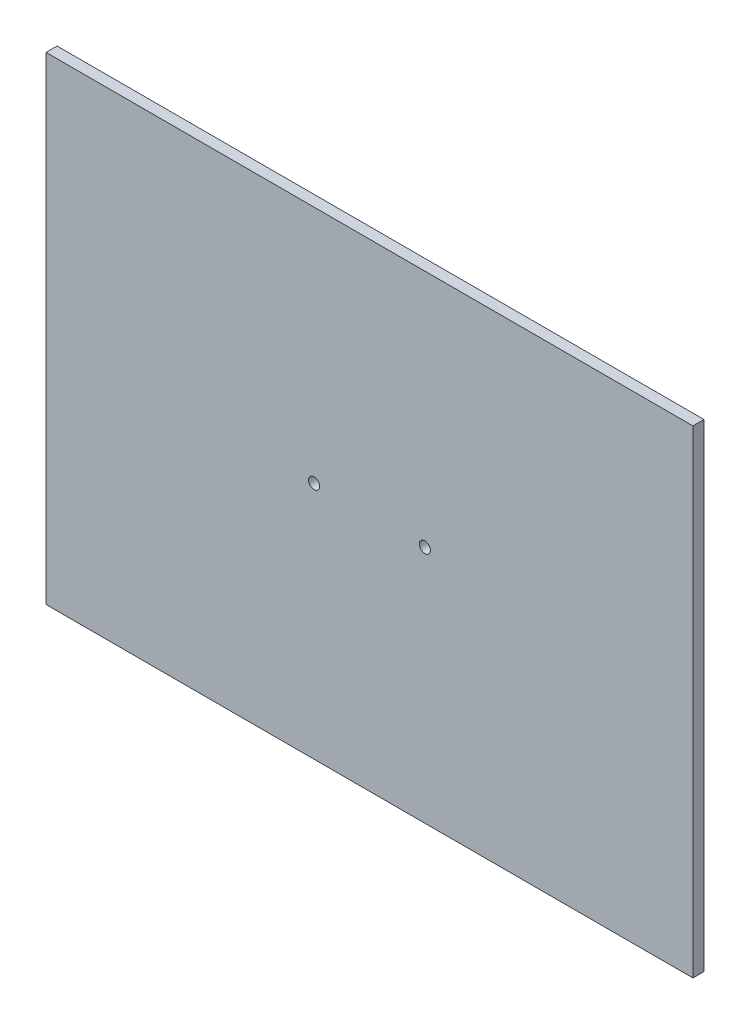
SolidWorks part; units mm, degrees
ref_plane "Front Plane" through (0, 0, 0) normal (0, 0, 1) x (1, 0, 0)
ref_plane "Top Plane" through (0, 0, 0) normal (0, 1, 0) x (1, 0, 0)
ref_plane "Right Plane" through (0, 0, 0) normal (1, 0, 0) x (0, 0, -1)
sketch "Sketch1" plane through (0, 0, 0) normal (0, 0, 1) x (1, 0, 0)
  line L1 (-146.05, -107.95) -> (146.05, -107.95)
  line L2 (-146.05, -107.95) -> (-146.05, 107.95)
  line L3 (-146.05, 107.95) -> (146.05, 107.95)
  line L4 (146.05, -107.95) -> (146.05, 107.95)
  line L5 (-146.05, -107.95) -> (146.05, 107.95) construction
  line L6 (-146.05, 107.95) -> (146.05, -107.95) construction
  point P0 (0, 0)
  dimension "D1" = 215.9
  dimension "D2" = 292.1
extrude "Boss-Extrude1" add sketch "Sketch1" along normal blind 5
sketch "Sketch2" plane through (0, 0, 0) normal (0, 0, -1) x (-1, 0, 0)
  line L1 (-25, -15) -> (25, -15) construction
  line L2 (-25, -15) -> (-25, 15) construction
  line L3 (-25, 15) -> (25, 15) construction
  line L4 (25, -15) -> (25, 15) construction
  line L5 (-25, -15) -> (25, 15) construction
  line L6 (-25, 15) -> (25, -15) construction
  circle A0 centre (-25, 0) radius 2.5
  circle A1 centre (25, 0) radius 2.5
  point P0 (0, 0)
  dimension "D3" = 5
  dimension "D1" = 50
  dimension "D2" = 30
extrude "Cut-Extrude1" cut sketch "Sketch2" against normal blind 5
